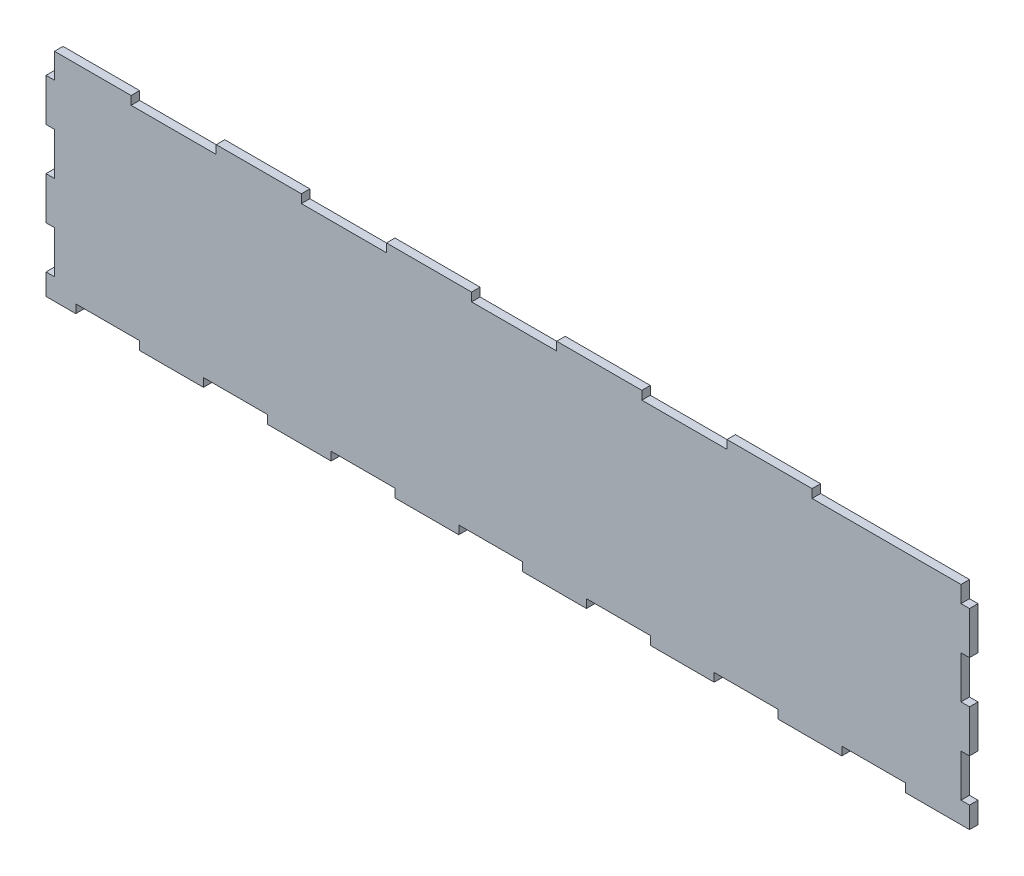
SolidWorks part; units mm, degrees
ref_plane "Front Plane" through (0, 0, 0) normal (0, 0, 1) x (1, 0, 0)
ref_plane "Top Plane" through (0, 0, 0) normal (0, 1, 0) x (1, 0, 0)
ref_plane "Right Plane" through (0, 0, 0) normal (1, 0, 0) x (0, 0, -1)
sketch "Sketch1" plane through (0, 0, 0) normal (0, 0, 1) x (1, 0, 0)
  line L1 (-137.7899, 31.0515) -> (137.7899, 31.0515)
  line L2 (-137.7899, 31.0515) -> (-137.7899, -31.0515)
  line L3 (-137.7899, -31.0515) -> (137.7899, -31.0515)
  line L4 (137.7899, 31.0515) -> (137.7899, -31.0515)
  line L5 (-137.7899, 31.0515) -> (137.7899, -31.0515) construction
  line L6 (-137.7899, -31.0515) -> (137.7899, 31.0515) construction
  point P0 (0, 0)
  dimension "D1" = 62.103
  dimension "D2" = 275.5798
extrude "Boss-Extrude1" add sketch "Sketch1" along normal blind 2.54
sketch "Sketch2" plane through (0, 0, 2.54) normal (0, 0, 1) x (1, 0, 0)
  line L1 (-137.7899, 31.0515) -> (-112.3899, 31.0515)
  line L2 (-137.7899, 31.0515) -> (-137.7899, 33.5915)
  line L3 (-137.7899, 33.5915) -> (-112.3899, 33.5915)
  line L4 (-112.3899, 31.0515) -> (-112.3899, 33.5915)
  dimension "D1" = 25.4
  dimension "D2" = 2.54
extrude "Boss-Extrude2" add sketch "Sketch2" against normal blind 2.54
pattern_linear "LPattern1" count 5 spacing 50.8 along (1, 0, 0) of "Boss-Extrude2"
sketch "Sketch3" plane through (0, 0, 2.54) normal (0, 0, 1) x (1, 0, 0)
  line L0 (-137.7899, 33.5915) -> (-137.7899, -31.0515) construction
  line L1 (-137.7899, -12.0015) -> (-135.2499, -12.0015)
  line L2 (-137.7899, -12.0015) -> (-137.7899, -24.7015)
  line L3 (-137.7899, -24.7015) -> (-135.2499, -24.7015)
  line L4 (-135.2499, -12.0015) -> (-135.2499, -24.7015)
  line L6 (-137.7899, -31.0515) -> (137.7899, -31.0515) construction
  dimension "D1" = 12.7
  dimension "D2" = 2.54
  dimension "D3" = 6.35
extrude "Cut-Extrude1" cut sketch "Sketch3" against normal through all
pattern_linear "LPattern3" count 3 spacing 25.4 along (0, 1, 0) of "Cut-Extrude1"
mirror "Mirror1" about plane through (0, 0, 0) normal (1, 0, 0) of "LPattern3", "Cut-Extrude1"
sketch "Sketch5" plane through (0, 0, 2.54) normal (0, 0, 1) x (1, 0, 0)
  line L0 (-137.7899, -31.0515) -> (137.7899, -31.0515) construction
  line L1 (-128.9101, -31.0515) -> (-109.8601, -31.0515)
  line L2 (-128.9101, -31.0515) -> (-128.9101, -28.5115)
  line L3 (-128.9101, -28.5115) -> (-109.8601, -28.5115)
  line L4 (-109.8601, -31.0515) -> (-109.8601, -28.5115)
  line L6 (-137.7899, -24.7015) -> (-137.7899, -31.0515) construction
  dimension "D1" = 19.05
  dimension "D2" = 2.54
  dimension "D3" = 8.8798
extrude "Cut-Extrude3" cut sketch "Sketch5" against normal through all
pattern_linear "LPattern5" count 8 spacing 38.1 along (1, 0, 0) of "Cut-Extrude3"
